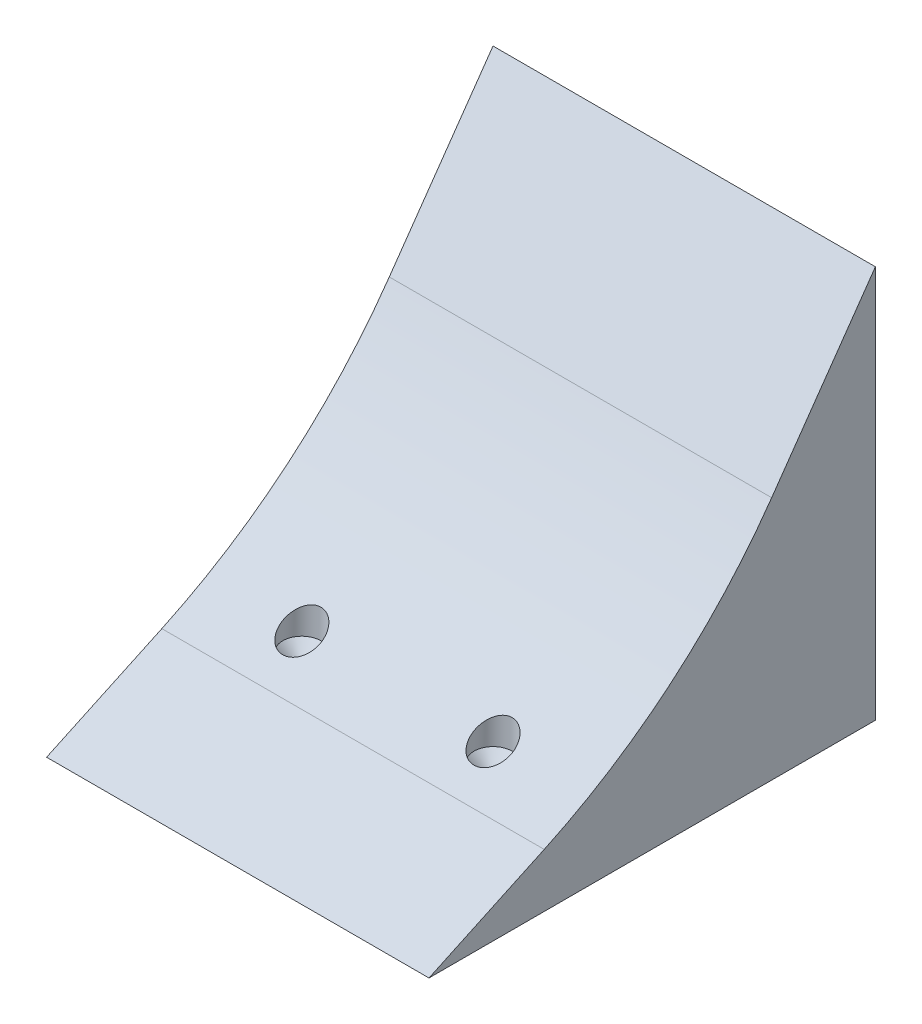
SolidWorks part; units mm, degrees
ref_plane "Front Plane" through (0, 0, 0) normal (0, 0, 1) x (1, 0, 0)
ref_plane "Top Plane" through (0, 0, 0) normal (0, 1, 0) x (1, 0, 0)
ref_plane "Right Plane" through (0, 0, 0) normal (1, 0, 0) x (0, 0, -1)
sketch "Sketch1" plane through (0, 0, 0) normal (1, 0, 0) x (0, 0, -1)
  line L0 (-61.4896, -124.3152) -> (57.1241, -124.3152)
  line L1 (57.1241, -124.3152) -> (57.1241, -19.9667)
  line L2 (29.5629, -59.3282) -> (57.1241, -19.9667)
  line L3 (-30.8689, -110.0365) -> (-61.4896, -124.3152)
  arc A0 (-30.8689, -110.0365) -> (29.5629, -59.3282) centre (-95.2759, 28.0848) ccw
  dimension "D2" = 152.4
  dimension "D1" = 55
  dimension "D3" = 25
extrude "Boss-Extrude1" add sketch "Sketch1" along normal blind 101.6
sketch "Sketch2" plane through (0, -124.3152, 0) normal (0, -1, 0) x (1, 0, 0)
  line L0 (25.4, 19.0759) -> (97.5645, 19.0759) construction
  line L1 (0, 61.4896) -> (0, -57.1241) construction
  line L2 (101.6, -57.1241) -> (0, -57.1241) construction
  circle A0 centre (25.4, 19.0759) radius 1.905
  circle A1 centre (76.2, 19.0759) radius 1.905
  point P4 (0, 0)
  point P6 (59.4946, 8.7016)
  dimension "D3" = 3.81
  dimension "D4" = 3.81
  dimension "D1" = 50.8
  dimension "D2" = 25.4
  dimension "D5" = 76.2
extrude "Cut-Extrude1" cut sketch "Sketch2" against normal blind 101.6
sketch "Sketch3" plane through (0, -124.3152, 0) normal (0, -1, 0) x (1, 0, 0)
  circle A0 centre (25.4, 19.0759) radius 5.08
  circle A1 centre (76.2, 19.0759) radius 5.08
  dimension "D1" = 10.16
  dimension "D2" = 10.16
extrude "Cut-Extrude2" cut sketch "Sketch3" against normal blind 101.6 from offset 12.7 offset against normal yes
chamfer "Chamfer1" distance 3.048 angle 45 2 edges at (76.2, -111.6152, 13.9959) (25.4, -111.6152, 13.9959)
